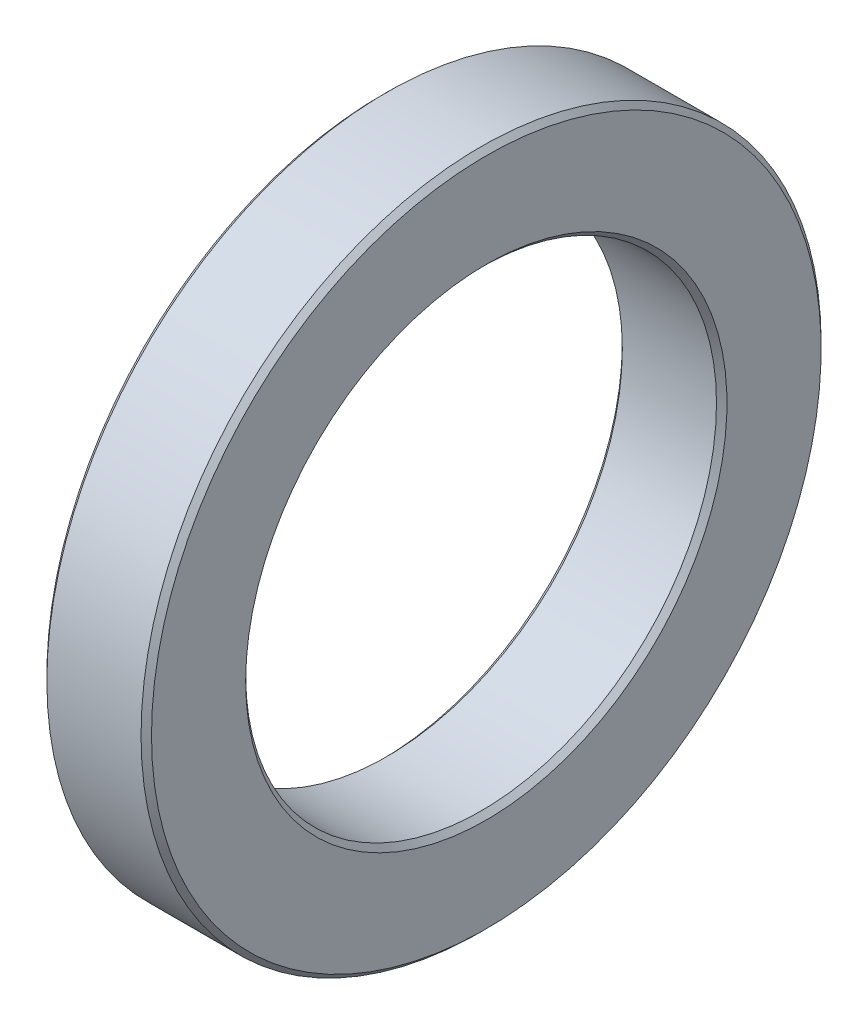
SolidWorks part; units mm, degrees
material "NEOPRENE"
ref_plane "Front Plane" through (0, 0, 0) normal (0, 0, 1) x (1, 0, 0)
ref_plane "Top Plane" through (0, 0, 0) normal (0, 1, 0) x (1, 0, 0)
ref_plane "Right Plane" through (0, 0, 0) normal (1, 0, 0) x (0, 0, -1)
sketch "Sketch1" plane through (0, 0, 0) normal (0, 0, 1) x (1, 0, 0)
  line L0 (0, 0) -> (10, 0) construction
  line L2 (0, 32.5) -> (10, 32.5)
  line L3 (0, 32.5) -> (0, 22.5)
  line L4 (0, 22.5) -> (10, 22.5)
  line L5 (10, 32.5) -> (10, 22.5)
  dimension "D1" = 10
  dimension "D2" = 45
  dimension "D3" = 65
revolve "Revolve1" add sketch "Sketch1" angle 360 about L0
chamfer "Chamfer1" distance 0.5 angle 45 4 edges at (0, 0, 22.5) (10, 0, 22.5) (0, 0, 32.5) (10, 0, 32.5)
